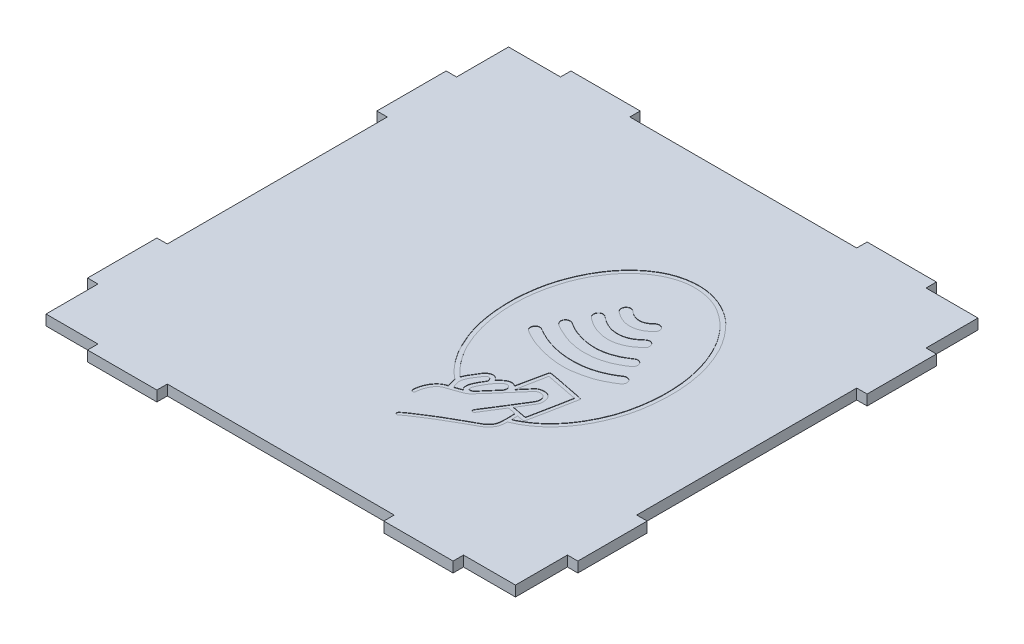
SolidWorks part; units mm, degrees
ref_plane "Спереди" through (0, 0, 0) normal (0, 0, 1) x (1, 0, 0)
ref_plane "Сверху" through (0, 0, 0) normal (0, 1, 0) x (1, 0, 0)
ref_plane "Справа" through (0, 0, 0) normal (1, 0, 0) x (0, 0, -1)
sketch "Sketch1" plane through (0, 0, 0) normal (0, 1, 0) x (1, 0, 0)
  line L0 (-47.661, 16.8006) -> (54.039, 16.8006) construction
  line L1 (-51.461, 56.8006) -> (84.039, 56.8006)
  line L2 (-51.461, 56.8006) -> (-51.461, -76.6994)
  line L3 (-51.461, -76.6994) -> (84.039, -76.6994)
  line L4 (84.039, 56.8006) -> (84.039, -76.6994)
  line L5 (54.039, -36.6994) -> (-47.661, -36.6994) construction
  line L6 (54.039, 16.8006) -> (54.039, -36.6994) construction
  point P0 (0, 0)
  dimension "D1" = 40
  dimension "D2" = 40
  dimension "D3" = 30
extrude "Boss-Extrude1" add sketch "Sketch1" along normal blind 3
sketch "Sketch2" plane through (0, 3, 0) normal (0, 1, 0) x (1, 0, 0)
  line L0 (84.039, -76.6994) -> (84.039, 56.8006) construction
  line L1 (84.039, 41.8006) -> (87.039, 41.8006)
  line L2 (84.039, 41.8006) -> (84.039, 21.8006)
  line L3 (84.039, 21.8006) -> (87.039, 21.8006)
  line L4 (87.039, 41.8006) -> (87.039, 21.8006)
  line L5 (84.039, 56.8006) -> (-51.461, 56.8006) construction
  line L6 (84.039, -41.6994) -> (87.039, -41.6994)
  line L7 (84.039, -41.6994) -> (84.039, -61.6994)
  line L8 (84.039, -61.6994) -> (87.039, -61.6994)
  line L9 (87.039, -41.6994) -> (87.039, -61.6994)
  line L10 (69.039, 56.8006) -> (49.039, 56.8006)
  line L11 (69.039, 56.8006) -> (69.039, 59.8006)
  line L12 (69.039, 59.8006) -> (49.039, 59.8006)
  line L13 (49.039, 56.8006) -> (49.039, 59.8006)
  line L14 (-51.461, 56.8006) -> (-51.461, -76.6994) construction
  line L15 (-16.461, 56.8006) -> (-36.461, 56.8006)
  line L16 (-16.461, 56.8006) -> (-16.461, 59.8006)
  line L17 (-16.461, 59.8006) -> (-36.461, 59.8006)
  line L18 (-36.461, 56.8006) -> (-36.461, 59.8006)
  line L19 (-51.461, 41.8006) -> (-54.461, 41.8006)
  line L20 (-51.461, 41.8006) -> (-51.461, 21.8006)
  line L21 (-51.461, 21.8006) -> (-54.461, 21.8006)
  line L22 (-54.461, 41.8006) -> (-54.461, 21.8006)
  line L23 (-51.461, -76.6994) -> (84.039, -76.6994) construction
  line L24 (-51.461, -61.6994) -> (-54.461, -61.6994)
  line L25 (-51.461, -61.6994) -> (-51.461, -41.6994)
  line L26 (-51.461, -41.6994) -> (-54.461, -41.6994)
  line L27 (-54.461, -61.6994) -> (-54.461, -41.6994)
  line L28 (-36.461, -76.6994) -> (-16.461, -76.6994)
  line L29 (-36.461, -76.6994) -> (-36.461, -79.6994)
  line L30 (-36.461, -79.6994) -> (-16.461, -79.6994)
  line L31 (-16.461, -76.6994) -> (-16.461, -79.6994)
  line L33 (49.039, -76.6994) -> (69.039, -76.6994)
  line L34 (49.039, -76.6994) -> (49.039, -79.6994)
  line L35 (49.039, -79.6994) -> (69.039, -79.6994)
  line L36 (69.039, -76.6994) -> (69.039, -79.6994)
  dimension "D1" = 3
  dimension "D2" = 20
  dimension "D3" = 15
  dimension "D4" = 15
  dimension "D5" = 15
  dimension "D6" = 15
  dimension "D7" = 15
  dimension "D8" = 15
  dimension "D9" = 15
  dimension "D10" = 15
extrude "Boss-Extrude2" add sketch "Sketch2" against normal through all
sketch "Sketch3" plane through (0, 3, 0) normal (0, 1, 0) x (1, 0, 0)
  line L0 (27.6815, -35.4244) -> (25.6743, -36.1233)
  line L1 (32.8317, -30.458) -> (30.3159, -33.3388)
  line L2 (39.355, -32.5485) -> (40.4082, -30.8417)
  line L3 (37.7112, -24.8084) -> (35.1838, -27.7573)
  line L4 (35.1081, -27.8307) -> (36.6747, -19.7)
  line L5 (36.6747, -19.7) -> (45.8332, -21.4827)
  line L6 (45.8332, -21.4827) -> (45.2819, -24.4901)
  line L7 (43.532, -33.3307) -> (39.355, -32.5485)
  line L8 (17.2059, -23.6162) -> (15.8427, -20.4235)
  line L9 (18.244, 11.9301) -> (20.0972, 14.7631)
  line L10 (50.4629, 15.7388) -> (52.1819, 13.418)
  line L11 (50.6783, -29.1122) -> (49.0377, -31.001)
  line L12 (42.1304, -35.8027) -> (42.0958, -34.1266)
  line L13 (35.7103, -19.4195) -> (34.1008, -27.0588)
  line L14 (34.1139, -30.5204) -> (36.4629, -27.7967)
  line L15 (37.0624, -27.1144) -> (38.2486, -25.7335)
  line L16 (29.0247, -46.8698) -> (26.4863, -48.5011)
  line L17 (24.8796, -50.8822) -> (25.7992, -50.1983)
  line L18 (30.8622, -46.9168) -> (36.1857, -43.8319)
  line L19 (50.6573, -30.9481) -> (52.0521, -29.2638)
  line L20 (52.3259, 15.2266) -> (50.2463, 17.7675)
  line L21 (25.7903, 21.7163) -> (24.4082, 20.7841)
  line L22 (19.3706, 15.7393) -> (18.1046, 13.9236)
  line L23 (19.302, -29.2859) -> (20.3278, -30.5687)
  line L24 (45.2819, -24.4901) -> (45.8332, -21.4827)
  line L25 (45.8332, -21.4827) -> (36.6747, -19.7)
  line L26 (36.6747, -19.7) -> (35.1081, -27.8307)
  line L27 (35.1838, -27.7573) -> (37.7112, -24.8084)
  line L28 (40.4082, -30.8417) -> (39.355, -32.5485)
  line L29 (39.355, -32.5485) -> (43.532, -33.3307)
  line L30 (44.336, -3.1903) -> (43.7409, -3.5574)
  line L31 (27.7984, -3.6478) -> (26.5484, -2.9045)
  line L32 (41.6305, -0.1032) -> (43.3413, 1.272)
  line L33 (30.3159, -33.3388) -> (32.8317, -30.458)
  line L34 (25.6743, -36.1233) -> (27.6815, -35.4244)
  spline S0 degree 3 poles (25.6743, -36.1233) (25.4135, -35.7279) (25.0815, -34.6524) (25.022, -34.0881) knots 0.090909 0.090909 0.090909 0.090909 0.181818 0.181818 0.181818 0.181818
  spline S1 degree 3 poles (25.022, -34.0881) (24.8631, -32.5818) (26.3191, -30.6929) (27.1134, -29.4207) knots 0.181818 0.181818 0.181818 0.181818 0.272727 0.272727 0.272727 0.272727
  spline S2 degree 3 poles (27.1134, -29.4207) (27.3012, -29.1199) (27.4494, -28.8589) (27.7815, -28.6863) knots 0.272727 0.272727 0.272727 0.272727 0.363636 0.363636 0.363636 0.363636
  spline S3 degree 3 poles (27.7815, -28.6863) (28.1347, -28.5029) (28.4442, -28.4746) (28.6886, -28.7569) knots 0.363636 0.363636 0.363636 0.363636 0.454545 0.454545 0.454545 0.454545
  spline S4 degree 3 poles (28.6886, -28.7569) (28.8217, -28.9107) (29.05, -29.4526) (28.9567, -29.7327) knots 0.454545 0.454545 0.454545 0.454545 0.545455 0.545455 0.545455 0.545455
  spline S5 degree 3 poles (28.9567, -29.7327) (28.9024, -29.896) (28.5775, -30.3586) (28.461, -30.5839) knots 0.545455 0.545455 0.545455 0.545455 0.636364 0.636364 0.636364 0.636364
  spline S6 degree 3 poles (28.461, -30.5839) (28.3097, -30.8767) (28.1357, -31.1528) (27.971, -31.4445) knots 0.636364 0.636364 0.636364 0.636364 0.727273 0.727273 0.727273 0.727273
  spline S7 degree 3 poles (27.971, -31.4445) (27.4915, -32.2942) (26.9121, -33.4811) (27.1448, -34.5329) knots 0.727273 0.727273 0.727273 0.727273 0.818182 0.818182 0.818182 0.818182
  spline S8 degree 3 poles (27.1448, -34.5329) (27.2517, -35.0159) (27.4423, -35.1142) (27.6815, -35.4244) knots 0.818182 0.818182 0.818182 0.818182 1 1 1 1
  spline S9 degree 3 poles (28.3546, -34.4692) (27.9472, -33.3259) (29.4463, -31.23) (30.0166, -30.273) knots 0 0 0 0 0.142857 0.142857 0.142857 0.142857
  spline S10 degree 3 poles (30.0166, -30.273) (30.4032, -29.6242) (32.3018, -26.9762) (33.3702, -27.9924) knots 0.142857 0.142857 0.142857 0.142857 0.285714 0.285714 0.285714 0.285714
  spline S11 degree 3 poles (33.3702, -27.9924) (33.6657, -28.2734) (33.7979, -28.5066) (33.7105, -29.0266) knots 0.285714 0.285714 0.285714 0.285714 0.428571 0.428571 0.428571 0.428571
  spline S12 degree 3 poles (33.7105, -29.0266) (33.5689, -29.8691) (33.3632, -29.8154) (32.8317, -30.458) knots 0.428571 0.428571 0.428571 0.428571 0.571429 0.571429 0.571429 0.571429
  spline S13 degree 3 poles (30.3159, -33.3388) (29.4749, -34.289) (29.3289, -34.6298) (28.3546, -34.4692) knots 0.714286 0.714286 0.714286 0.714286 1 1 1 1
  spline S14 degree 3 poles (40.4082, -30.8417) (40.7223, -30.3141) (41.1027, -29.655) (41.4485, -29.1192) knots 0.066667 0.066667 0.066667 0.066667 0.133333 0.133333 0.133333 0.133333
  spline S15 degree 3 poles (41.4485, -29.1192) (41.8684, -28.4687) (42.2133, -27.9976) (42.2517, -27.1537) knots 0.133333 0.133333 0.133333 0.133333 0.2 0.2 0.2 0.2
  spline S16 degree 3 poles (42.2517, -27.1537) (42.4207, -23.4321) (38.7472, -23.698) (37.7112, -24.8084) knots 0.2 0.2 0.2 0.2 0.266667 0.266667 0.266667 0.266667
  spline S17 degree 3 poles (35.1838, -27.7573) (35.1736, -27.7678) (35.1547, -27.7854) (35.1463, -27.7939) knots 0.333333 0.333333 0.333333 0.333333 0.4 0.4 0.4 0.4
  spline S18 degree 3 poles (35.1463, -27.7939) (35.1377, -27.8025) (35.1209, -27.8185) (35.1081, -27.8307) knots 0.4 0.4 0.4 0.4 0.466667 0.466667 0.466667 0.466667
  spline S19 degree 3 poles (45.2819, -24.4901) (45.0596, -25.4764) (44.9274, -26.4536) (44.7024, -27.4456) knots 0.666667 0.666667 0.666667 0.666667 0.733333 0.733333 0.733333 0.733333
  spline S20 degree 3 poles (44.7024, -27.4456) (44.4982, -28.3464) (44.2733, -29.4442) (44.115, -30.3812) knots 0.733333 0.733333 0.733333 0.733333 0.8 0.8 0.8 0.8
  spline S21 degree 3 poles (44.115, -30.3812) (43.9477, -31.371) (43.7102, -32.3577) (43.532, -33.3307) knots 0.8 0.8 0.8 0.8 0.866667 0.866667 0.866667 0.866667
  spline S22 degree 3 poles (34.1008, -27.0588) (33.9791, -26.8796) (33.3779, -26.6058) (32.9888, -26.5817) knots 0 0 0 0 0.026316 0.026316 0.026316 0.026316
  spline S23 degree 3 poles (32.9888, -26.5817) (32.0725, -26.5247) (31.3063, -27.0536) (30.7003, -27.618) knots 0.026316 0.026316 0.026316 0.026316 0.052632 0.052632 0.052632 0.052632
  spline S24 degree 3 poles (30.7003, -27.618) (30.5153, -27.7902) (30.0724, -28.194) (29.8817, -28.461) knots 0.052632 0.052632 0.052632 0.052632 0.078947 0.078947 0.078947 0.078947
  spline S25 degree 3 poles (29.8817, -28.461) (29.6817, -28.1704) (29.5397, -27.8753) (29.2036, -27.6656) knots 0.078947 0.078947 0.078947 0.078947 0.105263 0.105263 0.105263 0.105263
  spline S26 degree 3 poles (29.2036, -27.6656) (28.3843, -27.1543) (27.6854, -27.3381) (26.9089, -27.8704) knots 0.105263 0.105263 0.105263 0.105263 0.131579 0.131579 0.131579 0.131579
  spline S27 degree 3 poles (26.9089, -27.8704) (26.1964, -28.3587) (25.5426, -29.8189) (25.0451, -30.5656) knots 0.131579 0.131579 0.131579 0.131579 0.157895 0.157895 0.157895 0.157895
  spline S28 degree 3 poles (25.0451, -30.5656) (24.2917, -31.6965) (24.4853, -31.5598) (24.0052, -32.5841) knots 0.157895 0.157895 0.157895 0.157895 0.184211 0.184211 0.184211 0.184211
  spline S29 degree 3 poles (24.0052, -32.5841) (23.6042, -32.2899) (23.1798, -31.8848) (22.8294, -31.5364) knots 0.184211 0.184211 0.184211 0.184211 0.210526 0.210526 0.210526 0.210526
  spline S30 degree 3 poles (22.8294, -31.5364) (20.5767, -29.2963) (19.1308, -27.2192) (17.5994, -24.3803) knots 0.210526 0.210526 0.210526 0.210526 0.236842 0.236842 0.236842 0.236842
  spline S31 degree 3 poles (17.5994, -24.3803) (17.469, -24.1385) (17.3241, -23.8573) (17.2059, -23.6162) knots 0.236842 0.236842 0.236842 0.236842 0.263158 0.263158 0.263158 0.263158
  spline S32 degree 3 poles (15.8427, -20.4235) (13.3391, -13.491) (12.755, -5.4666) (14.3981, 1.7262) knots 0.289474 0.289474 0.289474 0.289474 0.315789 0.315789 0.315789 0.315789
  spline S33 degree 3 poles (14.3981, 1.7262) (14.8728, 3.8047) (15.7084, 6.9351) (16.6714, 8.8178) knots 0.315789 0.315789 0.315789 0.315789 0.342105 0.342105 0.342105 0.342105
  spline S34 degree 3 poles (16.6714, 8.8178) (17.2077, 9.8661) (17.6352, 10.9761) (18.244, 11.9301) knots 0.342105 0.342105 0.342105 0.342105 0.368421 0.368421 0.368421 0.368421
  spline S35 degree 3 poles (20.0972, 14.7631) (22.629, 18.2911) (26.5369, 21.4415) (30.8289, 22.7625) knots 0.394737 0.394737 0.394737 0.394737 0.421053 0.421053 0.421053 0.421053
  spline S36 degree 3 poles (30.8289, 22.7625) (33.695, 23.6446) (36.0648, 23.6767) (39.1085, 23.1233) knots 0.421053 0.421053 0.421053 0.421053 0.447368 0.447368 0.447368 0.447368
  spline S37 degree 3 poles (39.1085, 23.1233) (40.5655, 22.8585) (42.9014, 22.0082) (44.1739, 21.2008) knots 0.447368 0.447368 0.447368 0.447368 0.473684 0.473684 0.473684 0.473684
  spline S38 degree 3 poles (44.1739, 21.2008) (46.7617, 19.5588) (47.6506, 18.8317) (49.9051, 16.4033) knots 0.473684 0.473684 0.473684 0.473684 0.5 0.5 0.5 0.5
  spline S39 degree 3 poles (49.9051, 16.4033) (50.1626, 16.126) (50.2287, 16.0195) (50.4629, 15.7388) knots 0.5 0.5 0.5 0.5 0.526316 0.526316 0.526316 0.526316
  spline S40 degree 3 poles (52.1819, 13.418) (52.9551, 12.0946) (53.3023, 11.6069) (54.0718, 10.047) knots 0.552632 0.552632 0.552632 0.552632 0.578947 0.578947 0.578947 0.578947
  spline S41 degree 3 poles (54.0718, 10.047) (56.2941, 5.5426) (57.6087, 0.2228) (57.7879, -4.9486) knots 0.578947 0.578947 0.578947 0.578947 0.605263 0.605263 0.605263 0.605263
  spline S42 degree 3 poles (57.7879, -4.9486) (57.9137, -8.5787) (57.7785, -10.1996) (57.2673, -13.6154) knots 0.605263 0.605263 0.605263 0.605263 0.631579 0.631579 0.631579 0.631579
  spline S43 degree 3 poles (57.2673, -13.6154) (56.4125, -19.328) (54.153, -24.3671) (51.1758, -28.4535) knots 0.631579 0.631579 0.631579 0.631579 0.657895 0.657895 0.657895 0.657895
  spline S44 degree 3 poles (51.1758, -28.4535) (51.0084, -28.6832) (50.8623, -28.8901) (50.6783, -29.1122) knots 0.657895 0.657895 0.657895 0.657895 0.684211 0.684211 0.684211 0.684211
  spline S45 degree 3 poles (49.0377, -31.001) (48.2616, -31.7953) (47.4041, -32.5473) (46.5718, -33.217) knots 0.710526 0.710526 0.710526 0.710526 0.736842 0.736842 0.736842 0.736842
  spline S46 degree 3 poles (46.5718, -33.217) (45.7493, -33.8787) (42.9844, -35.6536) (42.1304, -35.8027) knots 0.736842 0.736842 0.736842 0.736842 0.763158 0.763158 0.763158 0.763158
  spline S47 degree 3 poles (42.0958, -34.1266) (42.6197, -34.1819) (44.0282, -34.664) (44.3349, -34.2532) knots 0.789474 0.789474 0.789474 0.789474 0.815789 0.815789 0.815789 0.815789
  spline S48 degree 3 poles (44.3349, -34.2532) (44.4642, -34.0799) (46.4105, -23.8671) (46.529, -23.2894) knots 0.815789 0.815789 0.815789 0.815789 0.842105 0.842105 0.842105 0.842105
  spline S49 degree 3 poles (46.529, -23.2894) (47.0177, -20.9061) (47.2629, -20.7465) (46.161, -20.525) knots 0.842105 0.842105 0.842105 0.842105 0.868421 0.868421 0.868421 0.868421
  spline S50 degree 3 poles (46.161, -20.525) (45.7846, -20.4493) (45.3997, -20.37) (45.038, -20.3056) knots 0.868421 0.868421 0.868421 0.868421 0.894737 0.894737 0.894737 0.894737
  spline S51 degree 3 poles (45.038, -20.3056) (43.9441, -20.1111) (36.5395, -18.5733) (36.2074, -18.6128) knots 0.894737 0.894737 0.894737 0.894737 0.921053 0.921053 0.921053 0.921053
  spline S52 degree 3 poles (36.2074, -18.6128) (35.7792, -18.6638) (35.7959, -18.9766) (35.7103, -19.4195) knots 0.921053 0.921053 0.921053 0.921053 0.947368 0.947368 0.947368 0.947368
  spline S53 degree 3 poles (24.5311, -36.5253) (23.9292, -36.6162) (23.2214, -37.0081) (22.8133, -37.3196) knots 0 0 0 0 0.013158 0.013158 0.013158 0.013158
  spline S54 degree 3 poles (22.8133, -37.3196) (21.3246, -38.4555) (20.371, -40.6943) (20.3327, -42.5609) knots 0.013158 0.013158 0.013158 0.013158 0.026316 0.026316 0.026316 0.026316
  spline S55 degree 3 poles (20.3327, -42.5609) (20.3236, -43.0081) (20.5808, -43.297) (21.023, -43.1222) knots 0.026316 0.026316 0.026316 0.026316 0.039474 0.039474 0.039474 0.039474
  spline S56 degree 3 poles (21.023, -43.1222) (21.3751, -42.983) (21.3073, -42.5788) (21.3691, -42.1722) knots 0.039474 0.039474 0.039474 0.039474 0.052632 0.052632 0.052632 0.052632
  spline S57 degree 3 poles (21.3691, -42.1722) (21.4714, -41.4988) (21.6746, -40.7523) (21.9364, -40.1653) knots 0.052632 0.052632 0.052632 0.052632 0.065789 0.065789 0.065789 0.065789
  spline S58 degree 3 poles (21.9364, -40.1653) (22.9799, -37.826) (24.1296, -37.6862) (26.4097, -36.9468) knots 0.065789 0.065789 0.065789 0.065789 0.078947 0.078947 0.078947 0.078947
  spline S59 degree 3 poles (26.4097, -36.9468) (27.0665, -36.7338) (27.6578, -36.4633) (28.2806, -36.2476) knots 0.078947 0.078947 0.078947 0.078947 0.092105 0.092105 0.092105 0.092105
  spline S60 degree 3 poles (28.2806, -36.2476) (29.1279, -35.9543) (29.2918, -35.8123) (29.8883, -35.2805) knots 0.092105 0.092105 0.092105 0.092105 0.105263 0.105263 0.105263 0.105263
  spline S61 degree 3 poles (29.8883, -35.2805) (30.6336, -34.6161) (32.6414, -32.1535) (33.5307, -31.2175) knots 0.105263 0.105263 0.105263 0.105263 0.118421 0.118421 0.118421 0.118421
  spline S62 degree 3 poles (33.5307, -31.2175) (33.7676, -30.9682) (33.871, -30.7928) (34.1139, -30.5204) knots 0.118421 0.118421 0.118421 0.118421 0.131579 0.131579 0.131579 0.131579
  spline S63 degree 3 poles (36.4629, -27.7967) (36.7241, -27.5142) (36.8848, -27.3405) (37.0624, -27.1144) knots 0.144737 0.144737 0.144737 0.144737 0.157895 0.157895 0.157895 0.157895
  spline S64 degree 3 poles (38.2486, -25.7335) (39.1688, -24.6078) (41.105, -24.8975) (41.2824, -26.5738) knots 0.171053 0.171053 0.171053 0.171053 0.184211 0.184211 0.184211 0.184211
  spline S65 degree 3 poles (41.2824, -26.5738) (41.4136, -27.8141) (40.2449, -29.0629) (39.6639, -30.1043) knots 0.184211 0.184211 0.184211 0.184211 0.197368 0.197368 0.197368 0.197368
  spline S66 degree 3 poles (39.6639, -30.1043) (39.0613, -31.1844) (38.3398, -32.2406) (37.7056, -33.2822) knots 0.197368 0.197368 0.197368 0.197368 0.210526 0.210526 0.210526 0.210526
  spline S67 degree 3 poles (37.7056, -33.2822) (37.0276, -34.3954) (36.3804, -35.3444) (35.7186, -36.4322) knots 0.210526 0.210526 0.210526 0.210526 0.223684 0.223684 0.223684 0.223684
  spline S68 degree 3 poles (35.7186, -36.4322) (35.244, -37.2121) (34.6459, -37.9715) (34.2216, -38.7883) knots 0.223684 0.223684 0.223684 0.223684 0.236842 0.236842 0.236842 0.236842
  spline S69 degree 3 poles (34.2216, -38.7883) (34.0402, -39.1376) (34.17, -39.5485) (34.5997, -39.5699) knots 0.236842 0.236842 0.236842 0.236842 0.25 0.25 0.25 0.25
  spline S70 degree 3 poles (34.5997, -39.5699) (35.0004, -39.5899) (35.1157, -39.262) (35.3109, -38.9683) knots 0.25 0.25 0.25 0.25 0.263158 0.263158 0.263158 0.263158
  spline S71 degree 3 poles (35.3109, -38.9683) (35.4962, -38.6896) (35.6209, -38.4516) (35.8034, -38.1751) knots 0.263158 0.263158 0.263158 0.263158 0.276316 0.276316 0.276316 0.276316
  spline S72 degree 3 poles (35.8034, -38.1751) (36.0892, -37.7423) (38.6037, -33.8491) (38.7626, -33.4564) knots 0.276316 0.276316 0.276316 0.276316 0.289474 0.289474 0.289474 0.289474
  spline S73 degree 3 poles (38.7626, -33.4564) (39.3365, -33.5724) (40.6186, -33.7501) (41.0812, -33.9554) knots 0.289474 0.289474 0.289474 0.289474 0.302632 0.302632 0.302632 0.302632
  spline S74 degree 3 poles (41.0812, -33.9554) (41.2099, -34.9677) (41.1652, -36.9512) (41.0875, -38.0037) knots 0.302632 0.302632 0.302632 0.302632 0.315789 0.315789 0.315789 0.315789
  spline S75 degree 3 poles (41.0875, -38.0037) (40.8907, -40.6704) (38.2841, -41.466) (36.3074, -42.5986) knots 0.315789 0.315789 0.315789 0.315789 0.328947 0.328947 0.328947 0.328947
  spline S76 degree 3 poles (36.3074, -42.5986) (36.058, -42.7416) (35.8514, -42.8601) (35.6165, -42.9956) knots 0.328947 0.328947 0.328947 0.328947 0.342105 0.342105 0.342105 0.342105
  spline S77 degree 3 poles (35.6165, -42.9956) (33.4735, -44.2307) (31.0723, -45.4978) (29.0247, -46.8698) knots 0.342105 0.342105 0.342105 0.342105 0.355263 0.355263 0.355263 0.355263
  spline S78 degree 3 poles (26.4863, -48.5011) (25.6634, -49.0614) (24.7602, -49.6182) (24.0297, -50.2857) knots 0.368421 0.368421 0.368421 0.368421 0.381579 0.381579 0.381579 0.381579
  spline S79 degree 3 poles (24.0297, -50.2857) (23.4754, -50.7922) (24.0117, -51.496) (24.6027, -51.1207) knots 0.381579 0.381579 0.381579 0.381579 0.394737 0.394737 0.394737 0.394737
  spline S80 degree 3 poles (24.6027, -51.1207) (24.6982, -51.0601) (24.7859, -50.9537) (24.8796, -50.8822) knots 0.394737 0.394737 0.394737 0.394737 0.407895 0.407895 0.407895 0.407895
  spline S81 degree 3 poles (25.7992, -50.1983) (27.6645, -48.8537) (29.1518, -48.0555) (30.8622, -46.9168) knots 0.421053 0.421053 0.421053 0.421053 0.434211 0.434211 0.434211 0.434211
  spline S82 degree 3 poles (36.1857, -43.8319) (37.3438, -43.0988) (39.1901, -42.362) (40.1774, -41.5289) knots 0.447368 0.447368 0.447368 0.447368 0.460526 0.460526 0.460526 0.460526
  spline S83 degree 3 poles (40.1774, -41.5289) (40.3803, -41.3577) (40.5137, -41.1983) (40.7079, -41.0283) knots 0.460526 0.460526 0.460526 0.460526 0.473684 0.473684 0.473684 0.473684
  spline S84 degree 3 poles (40.7079, -41.0283) (40.9524, -40.8143) (41.0196, -40.6761) (41.2044, -40.4324) knots 0.473684 0.473684 0.473684 0.473684 0.486842 0.486842 0.486842 0.486842
  spline S85 degree 3 poles (41.2044, -40.4324) (42.1777, -39.1491) (41.9024, -38.8) (42.1332, -37.1024) knots 0.486842 0.486842 0.486842 0.486842 0.5 0.5 0.5 0.5
  spline S86 degree 3 poles (42.1332, -37.1024) (42.6889, -36.7855) (43.5605, -36.4762) (44.2137, -36.1304) knots 0.5 0.5 0.5 0.5 0.513158 0.513158 0.513158 0.513158
  spline S87 degree 3 poles (44.2137, -36.1304) (45.5191, -35.4392) (46.781, -34.5475) (47.8971, -33.6499) knots 0.513158 0.513158 0.513158 0.513158 0.526316 0.526316 0.526316 0.526316
  spline S88 degree 3 poles (47.8971, -33.6499) (48.7571, -32.9582) (49.5551, -32.17) (50.3082, -31.374) knots 0.526316 0.526316 0.526316 0.526316 0.539474 0.539474 0.539474 0.539474
  spline S89 degree 3 poles (50.3082, -31.374) (50.4336, -31.2414) (50.5223, -31.0926) (50.6573, -30.9481) knots 0.539474 0.539474 0.539474 0.539474 0.552632 0.552632 0.552632 0.552632
  spline S90 degree 3 poles (52.0521, -29.2638) (53.1042, -27.9031) (53.9089, -26.478) (54.7482, -24.9586) knots 0.565789 0.565789 0.565789 0.565789 0.578947 0.578947 0.578947 0.578947
  spline S91 degree 3 poles (54.7482, -24.9586) (55.4615, -23.6673) (56.1005, -22.0794) (56.6346, -20.6785) knots 0.578947 0.578947 0.578947 0.578947 0.592105 0.592105 0.592105 0.592105
  spline S92 degree 3 poles (56.6346, -20.6785) (58.5257, -15.7186) (59.1627, -9.8538) (58.9305, -4.4921) knots 0.592105 0.592105 0.592105 0.592105 0.605263 0.605263 0.605263 0.605263
  spline S93 degree 3 poles (58.9305, -4.4921) (58.6279, 2.4935) (56.3336, 9.8388) (52.3259, 15.2266) knots 0.605263 0.605263 0.605263 0.605263 0.618421 0.618421 0.618421 0.618421
  spline S94 degree 3 poles (50.2463, 17.7675) (49.3203, 18.782) (48.1454, 19.9327) (46.9779, 20.7298) knots 0.631579 0.631579 0.631579 0.631579 0.644737 0.644737 0.644737 0.644737
  spline S95 degree 3 poles (46.9779, 20.7298) (46.8155, 20.8406) (46.7207, 20.9189) (46.5364, 21.0603) knots 0.644737 0.644737 0.644737 0.644737 0.657895 0.657895 0.657895 0.657895
  spline S96 degree 3 poles (46.5364, 21.0603) (45.9913, 21.4786) (44.7407, 22.1841) (44.1322, 22.503) knots 0.657895 0.657895 0.657895 0.657895 0.671053 0.671053 0.671053 0.671053
  spline S97 degree 3 poles (44.1322, 22.503) (42.322, 23.4519) (40.5093, 24.1053) (38.254, 24.4565) knots 0.671053 0.671053 0.671053 0.671053 0.684211 0.684211 0.684211 0.684211
  spline S98 degree 3 poles (38.254, 24.4565) (33.9433, 25.1276) (29.1307, 23.9807) (25.7903, 21.7163) knots 0.684211 0.684211 0.684211 0.684211 0.697368 0.697368 0.697368 0.697368
  spline S99 degree 3 poles (24.4082, 20.7841) (24.2297, 20.6545) (24.1382, 20.5835) (23.9777, 20.4474) knots 0.710526 0.710526 0.710526 0.710526 0.723684 0.723684 0.723684 0.723684
  spline S100 degree 3 poles (23.9777, 20.4474) (23.7917, 20.2898) (23.6969, 20.2086) (23.5606, 20.0928) knots 0.723684 0.723684 0.723684 0.723684 0.736842 0.736842 0.736842 0.736842
  spline S101 degree 3 poles (23.5606, 20.0928) (23.3722, 19.9326) (23.3186, 19.9173) (23.138, 19.7421) knots 0.736842 0.736842 0.736842 0.736842 0.75 0.75 0.75 0.75
  spline S102 degree 3 poles (23.138, 19.7421) (22.9159, 19.5266) (22.9076, 19.6182) (22.7108, 19.3999) knots 0.75 0.75 0.75 0.75 0.763158 0.763158 0.763158 0.763158
  spline S103 degree 3 poles (22.7108, 19.3999) (22.0955, 18.7174) (21.3447, 18.1737) (20.7578, 17.4353) knots 0.763158 0.763158 0.763158 0.763158 0.776316 0.776316 0.776316 0.776316
  spline S104 degree 3 poles (20.7578, 17.4353) (20.2974, 16.856) (19.8023, 16.3559) (19.3706, 15.7393) knots 0.776316 0.776316 0.776316 0.776316 0.789474 0.789474 0.789474 0.789474
  spline S105 degree 3 poles (18.1046, 13.9236) (16.3928, 11.347) (15.1387, 8.419) (14.1559, 5.4165) knots 0.802632 0.802632 0.802632 0.802632 0.815789 0.815789 0.815789 0.815789
  spline S106 degree 3 poles (14.1559, 5.4165) (13.7057, 4.0412) (13.1599, 1.9471) (12.95, 0.399) knots 0.815789 0.815789 0.815789 0.815789 0.828947 0.828947 0.828947 0.828947
  spline S107 degree 3 poles (12.95, 0.399) (12.688, -1.5326) (12.4345, -3.2028) (12.3656, -5.1977) knots 0.828947 0.828947 0.828947 0.828947 0.842105 0.842105 0.842105 0.842105
  spline S108 degree 3 poles (12.3656, -5.1977) (12.2928, -7.3072) (12.3858, -9.1646) (12.5606, -11.232) knots 0.842105 0.842105 0.842105 0.842105 0.855263 0.855263 0.855263 0.855263
  spline S109 degree 3 poles (12.5606, -11.232) (12.6392, -12.162) (12.821, -13.0421) (12.9375, -13.9527) knots 0.855263 0.855263 0.855263 0.855263 0.868421 0.868421 0.868421 0.868421
  spline S110 degree 3 poles (12.9375, -13.9527) (13.178, -15.8311) (14.1789, -19.5363) (14.9205, -21.2729) knots 0.868421 0.868421 0.868421 0.868421 0.881579 0.881579 0.881579 0.881579
  spline S111 degree 3 poles (14.9205, -21.2729) (16.1048, -24.0461) (17.1202, -26.3512) (18.9571, -28.7938) knots 0.881579 0.881579 0.881579 0.881579 0.894737 0.894737 0.894737 0.894737
  spline S112 degree 3 poles (18.9571, -28.7938) (19.0881, -28.968) (19.1543, -29.0949) (19.302, -29.2859) knots 0.894737 0.894737 0.894737 0.894737 0.907895 0.907895 0.907895 0.907895
  spline S113 degree 3 poles (20.3278, -30.5687) (20.4801, -30.7374) (20.5174, -30.8001) (20.6933, -30.9764) knots 0.921053 0.921053 0.921053 0.921053 0.934211 0.934211 0.934211 0.934211
  spline S114 degree 3 poles (20.6933, -30.9764) (20.9733, -31.2569) (21.0815, -31.4637) (21.4291, -31.7787) knots 0.934211 0.934211 0.934211 0.934211 0.947368 0.947368 0.947368 0.947368
  spline S115 degree 3 poles (21.4291, -31.7787) (21.7372, -32.0579) (21.9244, -32.2724) (22.2248, -32.5927) knots 0.947368 0.947368 0.947368 0.947368 0.960526 0.960526 0.960526 0.960526
  spline S116 degree 3 poles (22.2248, -32.5927) (22.502, -32.8884) (23.7796, -33.8433) (23.8451, -34.0452) knots 0.960526 0.960526 0.960526 0.960526 0.973684 0.973684 0.973684 0.973684
  spline S117 degree 3 poles (23.8451, -34.0452) (24.0633, -34.7171) (23.8555, -34.7284) (24.5311, -36.5253) knots 0.973684 0.973684 0.973684 0.973684 1 1 1 1
  spline S118 degree 3 poles (47.8214, -8.7131) (47.5096, -8.7942) (46.6173, -9.4045) (46.3213, -9.5973) knots 0 0 0 0 0.083333 0.083333 0.083333 0.083333
  spline S119 degree 3 poles (46.3213, -9.5973) (45.8634, -9.8956) (45.3081, -10.1656) (44.782, -10.4324) knots 0.083333 0.083333 0.083333 0.083333 0.166667 0.166667 0.166667 0.166667
  spline S120 degree 3 poles (44.782, -10.4324) (38.8592, -13.4368) (31.3385, -12.8243) (25.5227, -9.837) knots 0.166667 0.166667 0.166667 0.166667 0.25 0.25 0.25 0.25
  spline S121 degree 3 poles (25.5227, -9.837) (24.1287, -9.121) (23.244, -8.1985) (22.2606, -8.9717) knots 0.25 0.25 0.25 0.25 0.333333 0.333333 0.333333 0.333333
  spline S122 degree 3 poles (22.2606, -8.9717) (21.8497, -9.2947) (21.5088, -9.9995) (21.8847, -10.7176) knots 0.333333 0.333333 0.333333 0.333333 0.416667 0.416667 0.416667 0.416667
  spline S123 degree 3 poles (21.8847, -10.7176) (22.3368, -11.581) (25.5, -12.9394) (26.4405, -13.2954) knots 0.416667 0.416667 0.416667 0.416667 0.5 0.5 0.5 0.5
  spline S124 degree 3 poles (26.4405, -13.2954) (30.0641, -14.6672) (34.6819, -15.6706) (38.6308, -15.0811) knots 0.5 0.5 0.5 0.5 0.583333 0.583333 0.583333 0.583333
  spline S125 degree 3 poles (38.6308, -15.0811) (41.4523, -14.66) (43.7014, -14.1127) (45.997, -12.9456) knots 0.583333 0.583333 0.583333 0.583333 0.666667 0.666667 0.666667 0.666667
  spline S126 degree 3 poles (45.997, -12.9456) (46.8856, -12.4938) (48.2368, -11.7654) (49.0097, -11.2036) knots 0.666667 0.666667 0.666667 0.666667 0.75 0.75 0.75 0.75
  spline S127 degree 3 poles (49.0097, -11.2036) (49.4528, -10.8816) (49.7368, -10.1474) (49.4444, -9.4871) knots 0.75 0.75 0.75 0.75 0.833333 0.833333 0.833333 0.833333
  spline S128 degree 3 poles (49.4444, -9.4871) (49.1681, -8.8627) (48.4381, -8.5525) (47.8214, -8.7131) knots 0.833333 0.833333 0.833333 0.833333 1 1 1 1
  spline S129 degree 3 poles (43.532, -33.3307) (43.7102, -32.3577) (43.9477, -31.371) (44.115, -30.3812) knots 0 0 0 0 0.066667 0.066667 0.066667 0.066667
  spline S130 degree 3 poles (44.115, -30.3812) (44.2733, -29.4442) (44.4982, -28.3464) (44.7024, -27.4456) knots 0.066667 0.066667 0.066667 0.066667 0.133333 0.133333 0.133333 0.133333
  spline S131 degree 3 poles (44.7024, -27.4456) (44.9274, -26.4536) (45.0596, -25.4764) (45.2819, -24.4901) knots 0.133333 0.133333 0.133333 0.133333 0.2 0.2 0.2 0.2
  spline S132 degree 3 poles (35.1081, -27.8307) (35.1209, -27.8185) (35.1377, -27.8025) (35.1463, -27.7939) knots 0.4 0.4 0.4 0.4 0.466667 0.466667 0.466667 0.466667
  spline S133 degree 3 poles (35.1463, -27.7939) (35.1547, -27.7854) (35.1736, -27.7678) (35.1838, -27.7573) knots 0.466667 0.466667 0.466667 0.466667 0.533333 0.533333 0.533333 0.533333
  spline S134 degree 3 poles (37.7112, -24.8084) (38.7472, -23.698) (42.4207, -23.4321) (42.2517, -27.1537) knots 0.6 0.6 0.6 0.6 0.666667 0.666667 0.666667 0.666667
  spline S135 degree 3 poles (42.2517, -27.1537) (42.2133, -27.9976) (41.8684, -28.4687) (41.4485, -29.1192) knots 0.666667 0.666667 0.666667 0.666667 0.733333 0.733333 0.733333 0.733333
  spline S136 degree 3 poles (41.4485, -29.1192) (41.1027, -29.655) (40.7223, -30.3141) (40.4082, -30.8417) knots 0.733333 0.733333 0.733333 0.733333 0.8 0.8 0.8 0.8
  spline S137 degree 3 poles (46.7195, -3.8869) (46.5888, -3.3821) (46.5102, -3.0283) (45.8258, -2.8279) knots 0 0 0 0 0.071429 0.071429 0.071429 0.071429
  spline S138 degree 3 poles (45.8258, -2.8279) (45.1382, -2.6266) (44.7595, -2.8753) (44.336, -3.1903) knots 0.071429 0.071429 0.071429 0.071429 0.142857 0.142857 0.142857 0.142857
  spline S139 degree 3 poles (43.7409, -3.5574) (43.0838, -3.9303) (42.7285, -4.2268) (41.8482, -4.6098) knots 0.214286 0.214286 0.214286 0.214286 0.285714 0.285714 0.285714 0.285714
  spline S140 degree 3 poles (41.8482, -4.6098) (39.8128, -5.4951) (37.8542, -5.9969) (35.3011, -5.8748) knots 0.285714 0.285714 0.285714 0.285714 0.357143 0.357143 0.357143 0.357143
  spline S141 degree 3 poles (35.3011, -5.8748) (32.8209, -5.7561) (29.77, -4.8439) (27.7984, -3.6478) knots 0.357143 0.357143 0.357143 0.357143 0.428571 0.428571 0.428571 0.428571
  spline S142 degree 3 poles (26.5484, -2.9045) (24.9538, -2.1608) (23.4947, -4.3023) (25.4311, -5.506) knots 0.5 0.5 0.5 0.5 0.571429 0.571429 0.571429 0.571429
  spline S143 degree 3 poles (25.4311, -5.506) (25.8391, -5.7596) (26.2485, -6.0229) (26.6922, -6.2392) knots 0.571429 0.571429 0.571429 0.571429 0.642857 0.642857 0.642857 0.642857
  spline S144 degree 3 poles (26.6922, -6.2392) (29.7154, -7.7122) (32.3683, -8.6914) (36.0096, -8.6839) knots 0.642857 0.642857 0.642857 0.642857 0.714286 0.714286 0.714286 0.714286
  spline S145 degree 3 poles (36.0096, -8.6839) (38.4585, -8.6788) (40.5651, -8.1726) (42.5365, -7.3672) knots 0.714286 0.714286 0.714286 0.714286 0.785714 0.785714 0.785714 0.785714
  spline S146 degree 3 poles (42.5365, -7.3672) (43.496, -6.9752) (45.4861, -5.8994) (46.2562, -5.2387) knots 0.785714 0.785714 0.785714 0.785714 0.857143 0.857143 0.857143 0.857143
  spline S147 degree 3 poles (46.2562, -5.2387) (46.6076, -4.9371) (46.8641, -4.446) (46.7195, -3.8869) knots 0.857143 0.857143 0.857143 0.857143 1 1 1 1
  spline S148 degree 3 poles (41.9797, 3.6364) (41.4617, 3.4539) (40.8142, 2.7599) (40.242, 2.3176) knots 0 0 0 0 0.1 0.1 0.1 0.1
  spline S149 degree 3 poles (40.242, 2.3176) (38.2088, 0.7455) (35.4188, 0.4691) (33.0415, 1.4084) knots 0.1 0.1 0.1 0.1 0.2 0.2 0.2 0.2
  spline S150 degree 3 poles (33.0415, 1.4084) (30.6881, 2.3384) (29.9252, 3.5637) (29.1401, 3.6931) knots 0.2 0.2 0.2 0.2 0.3 0.3 0.3 0.3
  spline S151 degree 3 poles (29.1401, 3.6931) (28.1886, 3.8501) (27.4748, 3.1032) (27.5393, 2.1902) knots 0.3 0.3 0.3 0.3 0.4 0.4 0.4 0.4
  spline S152 degree 3 poles (27.5393, 2.1902) (27.5937, 1.421) (28.3746, 0.9253) (28.9284, 0.4925) knots 0.4 0.4 0.4 0.4 0.5 0.5 0.5 0.5
  spline S153 degree 3 poles (28.9284, 0.4925) (29.9061, -0.2717) (31.5719, -1.1219) (33.0628, -1.5388) knots 0.5 0.5 0.5 0.5 0.6 0.6 0.6 0.6
  spline S154 degree 3 poles (33.0628, -1.5388) (36.3334, -2.4532) (38.973, -1.8371) (41.6305, -0.1032) knots 0.6 0.6 0.6 0.6 0.7 0.7 0.7 0.7
  spline S155 degree 3 poles (43.3413, 1.272) (44.3423, 2.2103) (43.4544, 4.1556) (41.9797, 3.6364) knots 0.8 0.8 0.8 0.8 1 1 1 1
  spline S156 degree 3 poles (39.6045, 9.1079) (39.0157, 9.0568) (38.6062, 8.5451) (38.2729, 8.2656) knots 0 0 0 0 0.1 0.1 0.1 0.1
  spline S157 degree 3 poles (38.2729, 8.2656) (36.7717, 7.0068) (34.9579, 7.0754) (33.3998, 8.0485) knots 0.1 0.1 0.1 0.1 0.2 0.2 0.2 0.2
  spline S158 degree 3 poles (33.3998, 8.0485) (32.9509, 8.3288) (32.3919, 8.8645) (32.1534, 8.9897) knots 0.2 0.2 0.2 0.2 0.3 0.3 0.3 0.3
  spline S159 degree 3 poles (32.1534, 8.9897) (31.0134, 9.5882) (29.5837, 8.3415) (30.3191, 7.027) knots 0.3 0.3 0.3 0.3 0.4 0.4 0.4 0.4
  spline S160 degree 3 poles (30.3191, 7.027) (30.5468, 6.6199) (31.0506, 6.2788) (31.4349, 6.0152) knots 0.4 0.4 0.4 0.4 0.5 0.5 0.5 0.5
  spline S161 degree 3 poles (31.4349, 6.0152) (33.4673, 4.6213) (35.7552, 4.0386) (38.1586, 4.9678) knots 0.5 0.5 0.5 0.5 0.6 0.6 0.6 0.6
  spline S162 degree 3 poles (38.1586, 4.9678) (38.6965, 5.1758) (39.1664, 5.4594) (39.57, 5.7472) knots 0.6 0.6 0.6 0.6 0.7 0.7 0.7 0.7
  spline S163 degree 3 poles (39.57, 5.7472) (40.0102, 6.0611) (40.4211, 6.3434) (40.7688, 6.7333) knots 0.7 0.7 0.7 0.7 0.8 0.8 0.8 0.8
  spline S164 degree 3 poles (40.7688, 6.7333) (41.6566, 7.7285) (41.0292, 9.2313) (39.6045, 9.1079) knots 0.8 0.8 0.8 0.8 1 1 1 1
  spline S165 degree 3 poles (28.3546, -34.4692) (29.3289, -34.6298) (29.4749, -34.289) (30.3159, -33.3388) knots 0 0 0 0 0.142857 0.142857 0.142857 0.142857
  spline S166 degree 3 poles (32.8317, -30.458) (33.3632, -29.8154) (33.5689, -29.8691) (33.7105, -29.0266) knots 0.285714 0.285714 0.285714 0.285714 0.428571 0.428571 0.428571 0.428571
  spline S167 degree 3 poles (33.7105, -29.0266) (33.7979, -28.5066) (33.6657, -28.2734) (33.3702, -27.9924) knots 0.428571 0.428571 0.428571 0.428571 0.571429 0.571429 0.571429 0.571429
  spline S168 degree 3 poles (33.3702, -27.9924) (32.3018, -26.9762) (30.4032, -29.6242) (30.0166, -30.273) knots 0.571429 0.571429 0.571429 0.571429 0.714286 0.714286 0.714286 0.714286
  spline S169 degree 3 poles (30.0166, -30.273) (29.4463, -31.23) (27.9472, -33.3259) (28.3546, -34.4692) knots 0.714286 0.714286 0.714286 0.714286 1 1 1 1
  spline S170 degree 3 poles (27.6815, -35.4244) (27.4423, -35.1142) (27.2517, -35.0159) (27.1448, -34.5329) knots 0 0 0 0 0.090909 0.090909 0.090909 0.090909
  spline S171 degree 3 poles (27.1448, -34.5329) (26.9121, -33.4811) (27.4915, -32.2942) (27.971, -31.4445) knots 0.090909 0.090909 0.090909 0.090909 0.181818 0.181818 0.181818 0.181818
  spline S172 degree 3 poles (27.971, -31.4445) (28.1357, -31.1528) (28.3097, -30.8767) (28.461, -30.5839) knots 0.181818 0.181818 0.181818 0.181818 0.272727 0.272727 0.272727 0.272727
  spline S173 degree 3 poles (28.461, -30.5839) (28.5775, -30.3586) (28.9024, -29.896) (28.9567, -29.7327) knots 0.272727 0.272727 0.272727 0.272727 0.363636 0.363636 0.363636 0.363636
  spline S174 degree 3 poles (28.9567, -29.7327) (29.05, -29.4526) (28.8217, -28.9107) (28.6886, -28.7569) knots 0.363636 0.363636 0.363636 0.363636 0.454545 0.454545 0.454545 0.454545
  spline S175 degree 3 poles (28.6886, -28.7569) (28.4442, -28.4746) (28.1347, -28.5029) (27.7815, -28.6863) knots 0.454545 0.454545 0.454545 0.454545 0.545455 0.545455 0.545455 0.545455
  spline S176 degree 3 poles (27.7815, -28.6863) (27.4494, -28.8589) (27.3012, -29.1199) (27.1134, -29.4207) knots 0.545455 0.545455 0.545455 0.545455 0.636364 0.636364 0.636364 0.636364
  spline S177 degree 3 poles (27.1134, -29.4207) (26.3191, -30.6929) (24.8631, -32.5818) (25.022, -34.0881) knots 0.636364 0.636364 0.636364 0.636364 0.727273 0.727273 0.727273 0.727273
  spline S178 degree 3 poles (25.022, -34.0881) (25.0815, -34.6524) (25.4135, -35.7279) (25.6743, -36.1233) knots 0.727273 0.727273 0.727273 0.727273 0.818182 0.818182 0.818182 0.818182
extrude "Cut-Extrude1" cut sketch "Sketch3" against normal blind 0.1 contours S116 S117 S53 S54 S55 S56 S57 S58 S59 S60 S61 S62 L14 S63 L15 S64 S65 S66 S67 S68 S69 S70 S71 S72 S73 S74 S75 S76 S77 L16 S78 S79 S80 L17 S81 L18 S82 S83 S84 S85 S86 S87 S88 S89 L19 S90 S91 S92 S93 L20 S94 | S163 S164 S156 S157 S158 S159 S160 S161 S162 | L32 S155 S148 S149 S150 S151 S152 S153 S154 | S146 S147 S137 S138 L30 S139 S140 S141 L31 S142 S143 S144 S145 | S127 S128 S118 S119 S120 S121 S122 S123 S124 S125 S126
equation "\"D2@Sketch1\"=\"D1@Sketch1\""
equation "\"D4@Sketch2\"=\"D3@Sketch2\""
equation "\"D5@Sketch2\"=\"D3@Sketch2\""
equation "\"D6@Sketch2\"=\"D3@Sketch2\""
equation "\"D8@Sketch2\"=\"D3@Sketch2\""
equation "\"D9@Sketch2\"=\"D3@Sketch2\""
equation "\"D10@Sketch2\"=\"D3@Sketch2\""
equation "\"D7@Sketch2\"=\"D3@Sketch2\""
